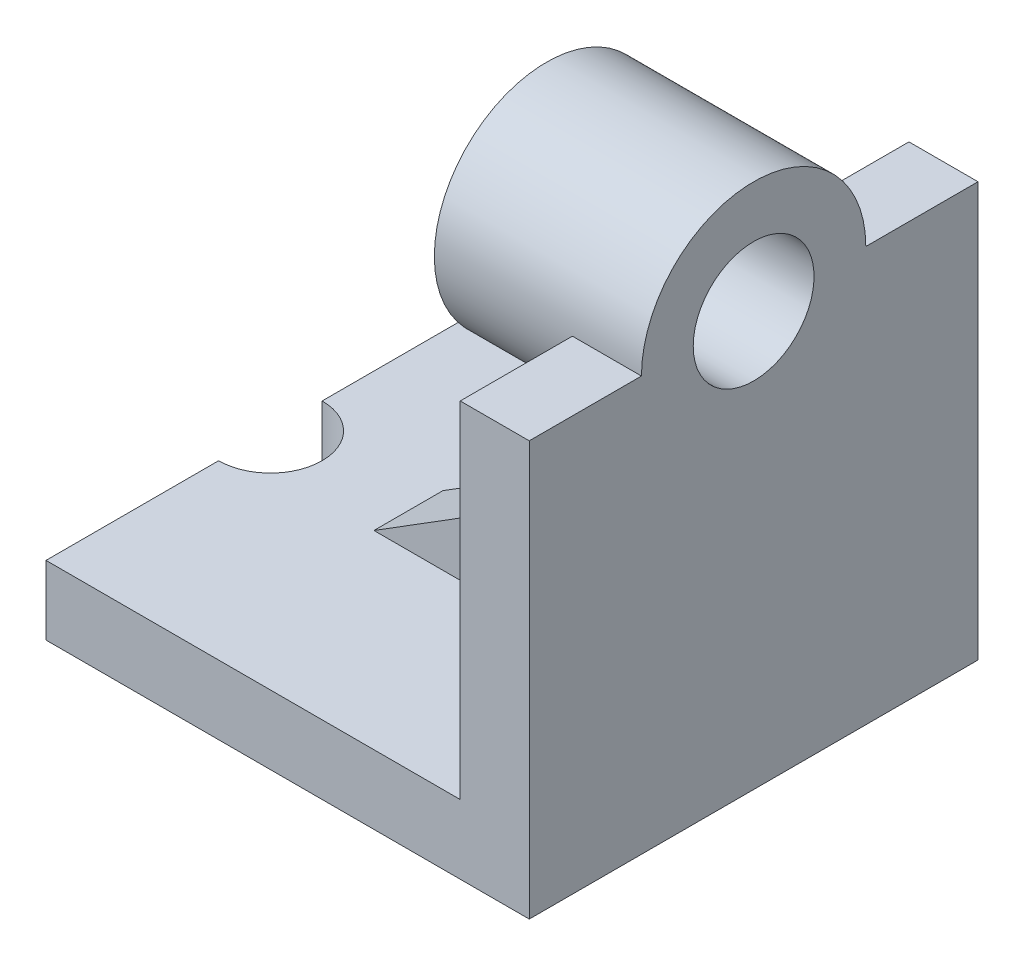
SolidWorks part; units mm, degrees
ref_plane "Спереди" through (0, 0, 0) normal (0, 0, 1) x (1, 0, 0)
ref_plane "Сверху" through (0, 0, 0) normal (0, 1, 0) x (1, 0, 0)
ref_plane "Справа" through (0, 0, 0) normal (1, 0, 0) x (0, 0, -1)
sketch "Эскиз1" plane through (0, 0, 0) normal (0, 0, 1) x (1, 0, 0)
  line L1 (-70, -10) -> (70, -10)
  line L2 (-70, -10) -> (-70, 10)
  line L3 (-70, 10) -> (70, 10)
  line L4 (70, -10) -> (70, 10)
  line L5 (-70, -10) -> (70, 10) construction
  line L6 (-70, 10) -> (70, -10) construction
  line L7 (70, 10) -> (50, 10)
  line L8 (70, 10) -> (70, 110)
  line L9 (70, 110) -> (50, 110)
  line L10 (50, 10) -> (50, 110)
  point P0 (0, 0)
  dimension "D1" = 140
  dimension "D2" = 20
  dimension "D3" = 120
extrude "Бобышка-Вытянуть1" add sketch "Эскиз1" along normal mid plane 130 contours L1 L4 L3 L2 | L8 L9 L10 L7
sketch "Эскиз5" plane through (70, 0, 0) normal (1, 0, 0) x (0, 0, -1)
  line L0 (-65, 110) -> (0, 110) construction
  line L1 (-65, 110) -> (65, 110) construction
  circle A0 centre (0, 110) radius 32.5
  dimension "D1" = 65
extrude "Бобышка-Вытянуть3" add sketch "Эскиз5" against normal blind 60
sketch "Эскиз6" plane through (10, 0, 0) normal (-1, 0, 0) x (0, 0, 1)
  circle A0 centre (0, 110) radius 17.5
  dimension "D1" = 35
extrude "Вырез-Вытянуть1" cut sketch "Эскиз6" against normal through all
sketch "Эскиз7" plane through (0, 10, 0) normal (0, 1, 0) x (1, 0, 0)
  line L0 (-70, -65) -> (-70, 65) construction
  circle A0 centre (-70, 0) radius 15
  dimension "D1" = 30
extrude "Вырез-Вытянуть2" cut sketch "Эскиз7" against normal through all
sketch "Эскиз8" plane through (0, 0, 0) normal (0, 0, 1) x (1, 0, 0)
  line L0 (-30, 10) -> (50, 60)
  line L1 (-70, 10) -> (50, 10) construction
  line L2 (50, 10) -> (50, 110) construction
  dimension "D1" = 80
rib "Ребро1" sketch "Эскиз8" sketch "Эскиз8" thickness 20 extrusion direction parallel to sketch draft on no parameters "D1"=20
